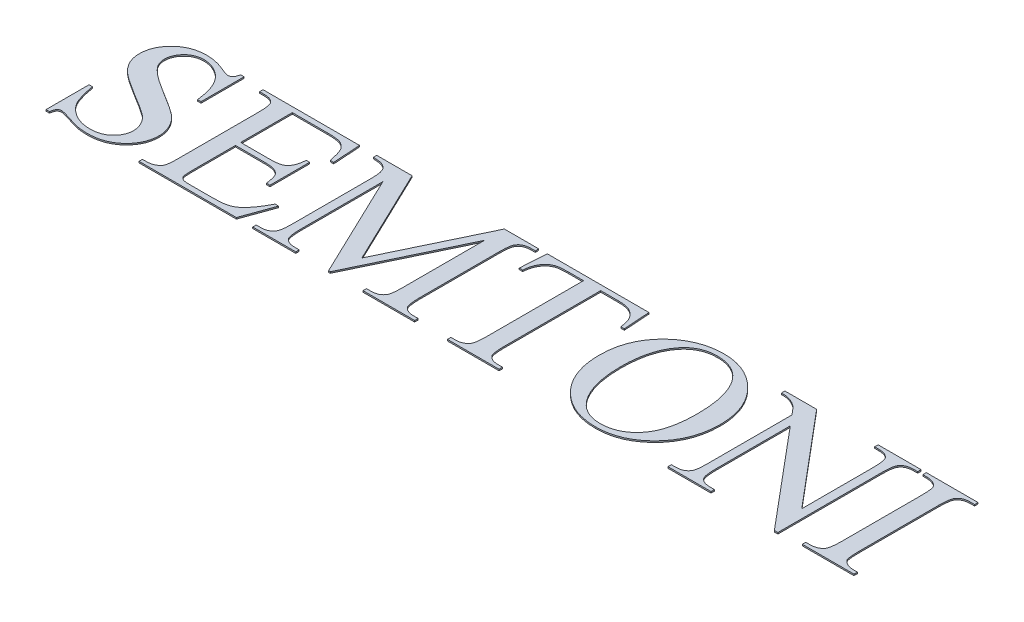
SolidWorks part; units mm, degrees
ref_plane "Спереди" through (0, 0, 0) normal (0, 0, 1) x (1, 0, 0)
ref_plane "Сверху" through (0, 0, 0) normal (0, 1, 0) x (1, 0, 0)
ref_plane "Справа" through (0, 0, 0) normal (1, 0, 0) x (0, 0, -1)
sketch "Эскиз1" plane through (0, 32.5739, 0) normal (0, 1, 0) x (1, 0, 0)
  text T0 "SEMTONI" font "Times New Roman" height in points 36
extrude "Бобышка-Вытянуть2" add sketch "Эскиз1" along normal blind 0.1
